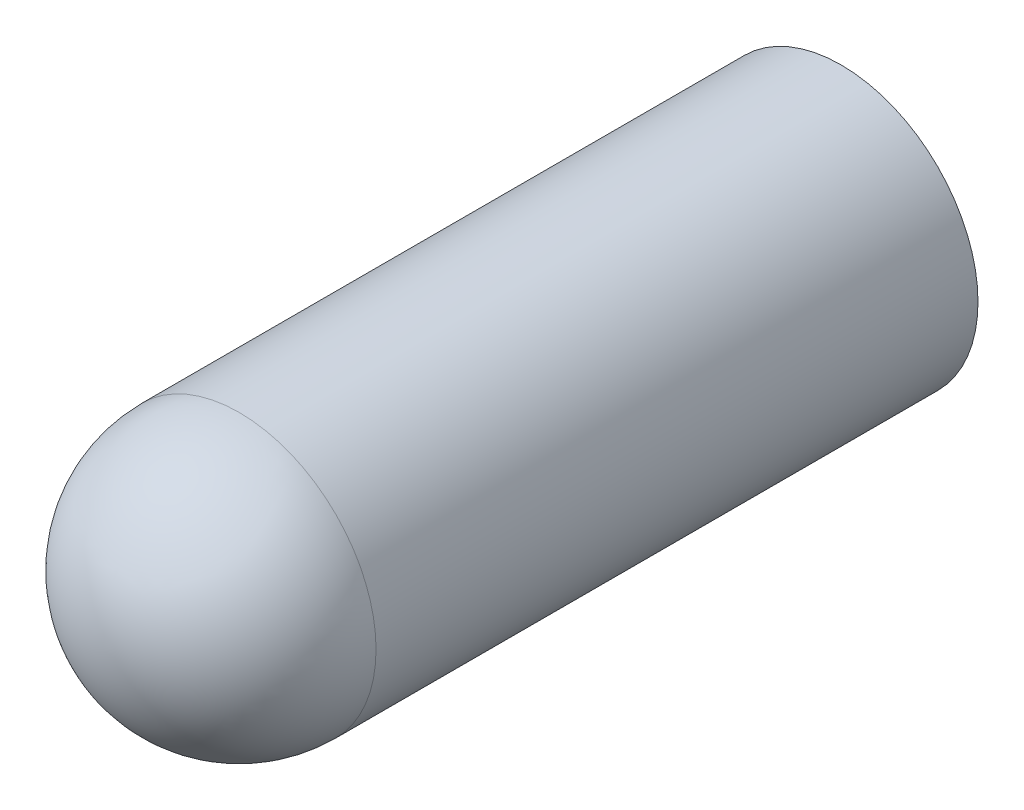
SolidWorks part; units mm, degrees
ref_plane "Face" through (0, 0, 0) normal (0, 0, 1) x (1, 0, 0)
ref_plane "Dessus" through (0, 0, 0) normal (0, 1, 0) x (1, 0, 0)
ref_plane "Droite" through (0, 0, 0) normal (1, 0, 0) x (0, 0, -1)
sketch "Esquisse1" plane through (0, 0, 0) normal (0, 0, 1) x (1, 0, 0)
  circle A0 centre (0, 0) radius 2.5
  dimension "D1" = 5
extrude "Extrusion1" add sketch "Esquisse1" along normal mid plane 11
sketch "Esquisse2" plane through (0, 0, 0) normal (1, 0, 0) x (0, 0, -1)
  line L0 (-5.5, 2.5) -> (-5.5, 0)
  line L1 (-5.5, 0) -> (-8, 0)
  line L4 (-5.5, 2.5) -> (-8.1065, 2.5) construction
  line L5 (-8, 0) -> (-8, 2.4433) construction
  arc A0 (-5.5, 2.5) -> (-8, 0) centre (-5.5, 0) ccw
  dimension "D1" = 2.5
revolve "Révolution1" add sketch "Esquisse2" angle 360 about L1
